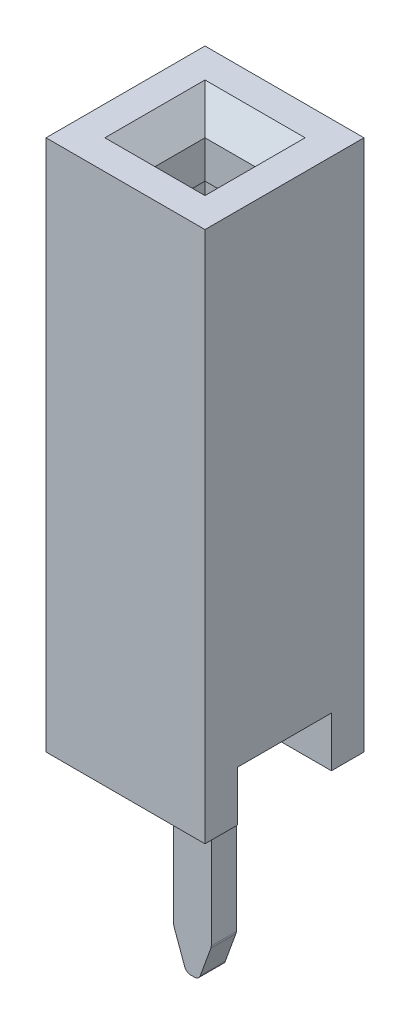
SolidWorks part; units mm, degrees
ref_plane "Спереди" through (0, 0, 0) normal (0, 0, 1) x (1, 0, 0)
ref_plane "Сверху" through (0, 0, 0) normal (0, 1, 0) x (1, 0, 0)
ref_plane "Справа" through (0, 0, 0) normal (1, 0, 0) x (0, 0, -1)
sketch "Sketch1" plane through (0, 0, 0) normal (0, 1, 0) x (1, 0, 0)
  line L1 (-1.27, 1.27) -> (1.27, 1.27) construction
  line L2 (-1.27, 1.27) -> (-1.27, -1.27) construction
  line L3 (-1.27, -1.27) -> (1.27, -1.27) construction
  line L4 (1.27, 1.27) -> (1.27, -1.27) construction
  line L5 (-1.27, 1.27) -> (1.27, -1.27) construction
  line L6 (-1.27, -1.27) -> (1.27, 1.27) construction
  line L7 (-0.3, 0.2) -> (0.3, 0.2) construction
  line L8 (-0.3, 0.2) -> (-0.3, -0.2) construction
  line L9 (-0.3, -0.2) -> (0.3, -0.2) construction
  line L10 (0.3, 0.2) -> (0.3, -0.2) construction
  line L11 (-0.3, 0.2) -> (0.3, -0.2) construction
  line L12 (-0.3, -0.2) -> (0.3, 0.2) construction
  point P0 (0, 0)
  point P6 (0, 0)
  dimension "D1" = 2.54
  dimension "D2" = 0.6
  dimension "D3" = 0.4
sketch "Sketch2" plane through (0, 0, 0) normal (0, 0, 1) x (1, 0, 0)
  line L0 (0, 0) -> (0, 1) construction
  line L1 (0, 1) -> (0, 8.5) construction
  line L2 (0, 0) -> (0, -3) construction
  point P4 (0, 0)
  point P6 (0, 0)
  point P7 (0, 0)
  point P8 (0, 0)
  point P9 (0, 0)
  point P10 (0, 0)
  point P11 (0, 0)
  point P12 (0, 0)
  point P13 (0, 0)
  point P14 (0, 0)
  point P15 (0, 0)
  point P16 (0, 0)
  dimension "D1" = 1
  dimension "A" = 8.5
  dimension "D2" = 3
sketch "Sketch3" plane through (0, 0, 0) normal (0, 1, 0) x (1, 0, 0)
  line L0 (-0.3, -0.2) -> (0.3, 0.2) construction
  line L1 (-1.27, -1.27) -> (1.27, -1.27)
  line L2 (-1.27, -1.27) -> (-1.27, 1.27)
  line L3 (-1.27, 1.27) -> (1.27, 1.27)
  line L4 (1.27, -1.27) -> (1.27, 1.27)
  line L5 (-1.27, -1.27) -> (1.27, 1.27) construction
  line L6 (-1.27, 1.27) -> (1.27, -1.27) construction
  line L7 (-0.3, -0.2) -> (0.3, -0.2)
  line L8 (-0.3, -0.2) -> (-0.3, 0.2)
  line L9 (-0.3, 0.2) -> (0.3, 0.2)
  line L10 (0.3, -0.2) -> (0.3, 0.2)
  line L11 (-0.3, -0.2) -> (0.3, 0.2) construction
  line L12 (-0.3, 0.2) -> (0.3, -0.2) construction
  point P0 (0, 0)
  point P7 (0, 0)
extrude "Boss-Extrude1" add sketch "Sketch3" along normal up to vertex (8.5 mm away) from vertex at 0 up to point (0, 8.5, 0) starting at point (0, 0, 0)
sketch "Sketch4" plane through (0, 8.5, 0) normal (0, 1, 0) x (1, 0, 0)
  line L1 (-0.4, -0.4) -> (0.4, -0.4)
  line L2 (-0.4, -0.4) -> (-0.4, 0.4)
  line L3 (-0.4, 0.4) -> (0.4, 0.4)
  line L4 (0.4, -0.4) -> (0.4, 0.4)
  line L5 (-0.4, -0.4) -> (0.4, 0.4) construction
  line L6 (-0.4, 0.4) -> (0.4, -0.4) construction
  point P0 (0, 0)
  dimension "D1" = 0.8
extrude "Cut-Extrude1" cut sketch "Sketch4" against normal up to vertex (7.5 mm away) up to point (0, 1, 0)
chamfer "Chamfer1" distance 0.4 angle 45 4 edges at (0.4, 8.5, 0) (0, 8.5, 0.4) (-0.4, 8.5, 0) (0, 8.5, -0.4)
sketch "Sketch5" plane through (0, 8.5, 0) normal (0, 1, 0) x (1, 0, 0)
  line L1 (-0.8, -0.8) -> (0.8, -0.8)
  line L2 (-0.8, -0.8) -> (-0.8, 0.8)
  line L3 (-0.8, 0.8) -> (0.8, 0.8)
  line L4 (0.8, -0.8) -> (0.8, 0.8)
  line L5 (-0.8, -0.8) -> (0.8, 0.8) construction
  line L6 (-0.8, 0.8) -> (0.8, -0.8) construction
  point P0 (0, 0)
extrude "Cut-Extrude3" cut sketch "Sketch5" against normal up to surface (6.5 mm away) from offset 1 up to face at (0, 1, 0) offset against normal yes
sketch "Sketch6" plane through (0, 0, 0) normal (0, -1, 0) x (1, 0, 0)
  line L0 (1.27, -1.27) -> (1.27, 1.27) construction
  line L1 (-1.27, -0.75) -> (1.27, -0.75)
  line L2 (-1.27, -0.75) -> (-1.27, 0.75)
  line L3 (-1.27, 0.75) -> (1.27, 0.75)
  line L4 (1.27, -0.75) -> (1.27, 0.75)
  line L5 (-1.27, -0.75) -> (1.27, 0.75) construction
  line L6 (-1.27, 0.75) -> (1.27, -0.75) construction
  point P0 (0, 0)
  dimension "D1" = 1.5
extrude "Cut-Extrude4" cut sketch "Sketch6" against normal blind 0.8
sketch "Sketch7" plane through (0, 0, 0) normal (0, 1, 0) x (1, 0, 0)
  line L1 (-0.3, 0.2) -> (0.3, 0.2)
  line L2 (-0.3, 0.2) -> (-0.3, -0.2)
  line L3 (-0.3, -0.2) -> (0.3, -0.2)
  line L4 (0.3, 0.2) -> (0.3, -0.2)
  line L5 (-0.3, 0.2) -> (0.3, -0.2) construction
  line L6 (-0.3, -0.2) -> (0.3, 0.2) construction
  point P0 (0, 0)
extrude "Boss-Extrude2" add sketch "Sketch7" against normal up to vertex (3 mm away) from vertex at 1 separate body starting at point (0, 1, 0)
chamfer "Chamfer2" distance 0.2 angle 70 2 edges at (-0.3, -3, 0) (0.3, -3, 0)
fillet "Fillet1" radius 0.1 4 edges at (-0.1, -3, 0) (0.1, -3, 0) (0.3, -2.4505, 0) (-0.3, -2.4505, 0)
